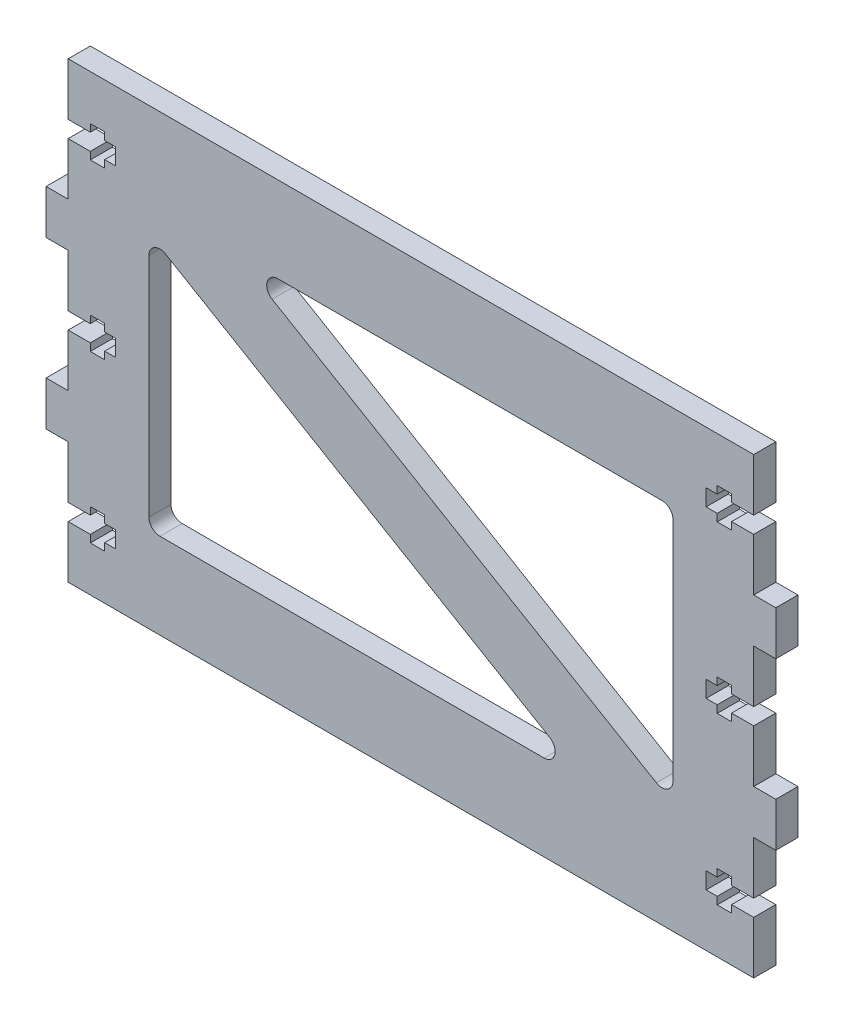
SolidWorks part; units mm, degrees
ref_plane "前视基准面" through (0, 0, 0) normal (0, 0, 1) x (1, 0, 0)
ref_plane "上视基准面" through (0, 0, 0) normal (0, 1, 0) x (1, 0, 0)
ref_plane "右视基准面" through (0, 0, 0) normal (1, 0, 0) x (0, 0, -1)
sketch "草图1" plane through (0, 0, 0) normal (0, 0, 1) x (1, 0, 0)
  line L0 (54.5343, 5.23) -> (-69.4657, 5.23) construction
  line L1 (58.5343, 20.23) -> (56.8313, 20.23) construction
  line L2 (46.9343, -24.77) -> (49.8557, -24.77) construction
  line L3 (59.5343, -9.77) -> (57.8313, -9.77) construction
  line L4 (54.5343, 3.73) -> (54.5343, 6.73) construction
  line L5 (54.5343, 5.23) -> (55.8421, 5.23) construction
  line L6 (54.5343, 6.73) -> (50.5343, 6.73)
  line L7 (50.5343, 6.73) -> (50.5343, 8.08)
  line L8 (50.5343, 8.08) -> (47.9343, 8.08)
  line L9 (47.9343, 8.08) -> (47.9343, 6.73)
  line L10 (47.9343, 6.73) -> (45.9343, 6.73)
  line L11 (47.9343, 2.38) -> (47.9343, 3.73)
  line L12 (50.5343, 3.73) -> (50.5343, 2.38)
  line L13 (47.9343, 3.73) -> (45.9343, 3.73)
  line L14 (50.5343, 2.38) -> (47.9343, 2.38)
  line L15 (54.5343, 3.73) -> (50.5343, 3.73)
  line L16 (54.5343, 24.23) -> (58.5343, 24.23)
  line L17 (58.5343, 24.23) -> (58.5343, 16.23)
  line L18 (58.5343, 16.23) -> (54.5343, 16.23)
  line L19 (54.5343, 16.23) -> (54.5343, 6.73)
  line L20 (-7.4657, 5.23) -> (-7.4657, 11.8034) construction
  line L21 (54.5343, 6.73) -> (50.5343, 6.73)
  line L22 (50.5343, 8.08) -> (47.9343, 8.08)
  line L23 (54.5343, 6.73) -> (50.5343, 6.73)
  line L24 (50.5343, 6.73) -> (50.5343, 8.08)
  line L25 (50.5343, 8.08) -> (47.9343, 8.08)
  line L26 (47.9343, 8.08) -> (47.9343, 6.73)
  line L27 (47.9343, 6.73) -> (45.9343, 6.73)
  line L28 (47.9343, 2.38) -> (47.9343, 3.73)
  line L29 (50.5343, 3.73) -> (50.5343, 2.38)
  line L30 (47.9343, 3.73) -> (45.9343, 3.73)
  line L31 (50.5343, 2.38) -> (47.9343, 2.38)
  line L32 (54.5343, 3.73) -> (50.5343, 3.73)
  line L33 (47.9343, 6.73) -> (45.9343, 6.73)
  line L34 (50.5343, 6.73) -> (50.5343, 8.08)
  line L35 (47.9343, 8.08) -> (47.9343, 6.73)
  line L36 (47.9343, 3.73) -> (45.9343, 3.73)
  line L37 (47.9343, 2.38) -> (47.9343, 3.73)
  line L38 (50.5343, 2.38) -> (47.9343, 2.38)
  line L39 (50.5343, 3.73) -> (50.5343, 2.38)
  line L40 (54.5343, 3.73) -> (50.5343, 3.73)
  line L41 (54.5343, -23.27) -> (54.5343, -13.77)
  line L42 (50.5343, -23.27) -> (54.5343, -23.27)
  line L43 (50.5343, -26.27) -> (54.5343, -26.27)
  line L44 (54.5343, -35.77) -> (54.5343, -26.27)
  line L45 (50.5343, -23.27) -> (50.5343, -21.92)
  line L46 (50.5343, -21.92) -> (47.9343, -21.92)
  line L47 (47.9343, -21.92) -> (47.9343, -23.27)
  line L48 (47.9343, -23.27) -> (45.9343, -23.27)
  line L49 (45.9343, -23.27) -> (45.9343, -26.27)
  line L50 (47.9343, -27.62) -> (47.9343, -26.27)
  line L51 (50.5343, -26.27) -> (50.5343, -27.62)
  line L52 (47.9343, -26.27) -> (45.9343, -26.27)
  line L53 (50.5343, -27.62) -> (47.9343, -27.62)
  line L54 (54.5343, -5.77) -> (54.5343, 3.73)
  line L55 (58.5343, -5.77) -> (54.5343, -5.77)
  line L56 (58.5343, -13.77) -> (58.5343, -5.77)
  line L57 (54.5343, -13.77) -> (58.5343, -13.77)
  line L58 (54.5343, 6.73) -> (50.5343, 6.73)
  line L59 (50.5343, 8.08) -> (47.9343, 8.08)
  line L60 (47.9343, 6.73) -> (45.9343, 6.73)
  line L61 (50.5343, 6.73) -> (50.5343, 8.08)
  line L62 (47.9343, 8.08) -> (47.9343, 6.73)
  line L63 (45.9343, 3.73) -> (45.9343, 6.73)
  line L64 (47.9343, 3.73) -> (45.9343, 3.73)
  line L65 (47.9343, 2.38) -> (47.9343, 3.73)
  line L66 (50.5343, 2.38) -> (47.9343, 2.38)
  line L67 (50.5343, 3.73) -> (50.5343, 2.38)
  line L68 (54.5343, 3.73) -> (50.5343, 3.73)
  line L69 (46.9343, 35.23) -> (49.8557, 35.23) construction
  line L70 (50.5343, 38.08) -> (47.9343, 38.08)
  line L71 (47.9343, 36.73) -> (45.9343, 36.73)
  line L72 (50.5343, 36.73) -> (50.5343, 38.08)
  line L73 (47.9343, 38.08) -> (47.9343, 36.73)
  line L74 (45.9343, 33.73) -> (45.9343, 36.73)
  line L75 (47.9343, 33.73) -> (45.9343, 33.73)
  line L76 (47.9343, 32.38) -> (47.9343, 33.73)
  line L77 (50.5343, 32.38) -> (47.9343, 32.38)
  line L78 (50.5343, 33.73) -> (50.5343, 32.38)
  line L79 (54.5343, 46.23) -> (54.5343, 36.73)
  line L80 (50.5343, 36.73) -> (54.5343, 36.73)
  line L81 (50.5343, 33.73) -> (54.5343, 33.73)
  line L82 (54.5343, 33.73) -> (54.5343, 24.23)
  line L83 (-61.8657, 35.23) -> (-64.7872, 35.23) construction
  line L84 (-69.4657, 5.23) -> (-70.7735, 5.23) construction
  line L85 (-69.4657, 3.73) -> (-69.4657, 6.73) construction
  line L86 (-74.4657, -9.77) -> (-72.7628, -9.77) construction
  line L87 (-61.8657, -24.77) -> (-64.7872, -24.77) construction
  line L88 (-73.4657, 20.23) -> (-71.7628, 20.23) construction
  line L89 (-69.4657, 33.73) -> (-69.4657, 24.23)
  line L90 (-65.4657, 33.73) -> (-69.4657, 33.73)
  line L91 (-65.4657, 36.73) -> (-69.4657, 36.73)
  line L92 (-69.4657, 46.23) -> (-69.4657, 36.73)
  line L93 (-65.4657, 33.73) -> (-65.4657, 32.38)
  line L94 (-65.4657, 32.38) -> (-62.8657, 32.38)
  line L95 (-62.8657, 32.38) -> (-62.8657, 33.73)
  line L96 (-62.8657, 33.73) -> (-60.8657, 33.73)
  line L97 (-60.8657, 33.73) -> (-60.8657, 36.73)
  line L98 (-62.8657, 38.08) -> (-62.8657, 36.73)
  line L99 (-65.4657, 36.73) -> (-65.4657, 38.08)
  line L100 (-62.8657, 36.73) -> (-60.8657, 36.73)
  line L101 (-65.4657, 38.08) -> (-62.8657, 38.08)
  line L102 (-69.4657, 3.73) -> (-65.4657, 3.73)
  line L103 (-65.4657, 3.73) -> (-65.4657, 2.38)
  line L104 (-65.4657, 2.38) -> (-62.8657, 2.38)
  line L105 (-62.8657, 2.38) -> (-62.8657, 3.73)
  line L106 (-62.8657, 3.73) -> (-60.8657, 3.73)
  line L107 (-60.8657, 3.73) -> (-60.8657, 6.73)
  line L108 (-62.8657, 8.08) -> (-62.8657, 6.73)
  line L109 (-65.4657, 6.73) -> (-65.4657, 8.08)
  line L110 (-62.8657, 6.73) -> (-60.8657, 6.73)
  line L111 (-65.4657, 8.08) -> (-62.8657, 8.08)
  line L112 (-69.4657, 6.73) -> (-65.4657, 6.73)
  line L113 (-69.4657, -13.77) -> (-73.4657, -13.77)
  line L114 (-73.4657, -13.77) -> (-73.4657, -5.77)
  line L115 (-73.4657, -5.77) -> (-69.4657, -5.77)
  line L116 (-69.4657, -5.77) -> (-69.4657, 3.73)
  line L117 (-65.4657, -27.62) -> (-62.8657, -27.62)
  line L118 (-62.8657, -26.27) -> (-60.8657, -26.27)
  line L119 (-65.4657, -26.27) -> (-65.4657, -27.62)
  line L120 (-62.8657, -27.62) -> (-62.8657, -26.27)
  line L121 (-60.8657, -23.27) -> (-60.8657, -26.27)
  line L122 (-62.8657, -23.27) -> (-60.8657, -23.27)
  line L123 (-62.8657, -21.92) -> (-62.8657, -23.27)
  line L124 (-65.4657, -21.92) -> (-62.8657, -21.92)
  line L125 (-65.4657, -23.27) -> (-65.4657, -21.92)
  line L126 (-69.4657, -35.77) -> (-69.4657, -26.27)
  line L127 (-65.4657, -26.27) -> (-69.4657, -26.27)
  line L128 (-65.4657, -23.27) -> (-69.4657, -23.27)
  line L129 (-69.4657, -23.27) -> (-69.4657, -13.77)
  line L130 (-69.4657, 3.73) -> (-65.4657, 3.73)
  line L131 (-65.4657, 3.73) -> (-65.4657, 2.38)
  line L132 (-65.4657, 2.38) -> (-62.8657, 2.38)
  line L133 (-62.8657, 2.38) -> (-62.8657, 3.73)
  line L134 (-62.8657, 3.73) -> (-60.8657, 3.73)
  line L135 (-62.8657, 8.08) -> (-62.8657, 6.73)
  line L136 (-65.4657, 6.73) -> (-65.4657, 8.08)
  line L137 (-62.8657, 6.73) -> (-60.8657, 6.73)
  line L138 (-69.4657, 3.73) -> (-65.4657, 3.73)
  line L139 (-65.4657, 2.38) -> (-62.8657, 2.38)
  line L140 (-62.8657, 3.73) -> (-60.8657, 3.73)
  line L141 (-65.4657, 3.73) -> (-65.4657, 2.38)
  line L142 (-62.8657, 2.38) -> (-62.8657, 3.73)
  line L143 (-62.8657, 6.73) -> (-60.8657, 6.73)
  line L144 (-62.8657, 8.08) -> (-62.8657, 6.73)
  line L145 (-65.4657, 8.08) -> (-62.8657, 8.08)
  line L146 (-65.4657, 6.73) -> (-65.4657, 8.08)
  line L147 (-69.4657, 6.73) -> (-65.4657, 6.73)
  line L148 (-65.4657, 8.08) -> (-62.8657, 8.08)
  line L149 (-69.4657, 6.73) -> (-65.4657, 6.73)
  line L150 (-69.4657, 16.23) -> (-69.4657, 6.73)
  line L151 (-73.4657, 16.23) -> (-69.4657, 16.23)
  line L152 (-73.4657, 24.23) -> (-73.4657, 16.23)
  line L153 (-69.4657, 24.23) -> (-73.4657, 24.23)
  line L154 (-69.4657, 3.73) -> (-65.4657, 3.73)
  line L155 (-65.4657, 2.38) -> (-62.8657, 2.38)
  line L156 (-62.8657, 3.73) -> (-60.8657, 3.73)
  line L157 (-65.4657, 3.73) -> (-65.4657, 2.38)
  line L158 (-62.8657, 2.38) -> (-62.8657, 3.73)
  line L159 (-62.8657, 6.73) -> (-60.8657, 6.73)
  line L160 (-62.8657, 8.08) -> (-62.8657, 6.73)
  line L161 (-65.4657, 8.08) -> (-62.8657, 8.08)
  line L162 (-65.4657, 6.73) -> (-65.4657, 8.08)
  line L163 (-69.4657, 6.73) -> (-65.4657, 6.73)
  line L164 (-69.4657, 46.23) -> (54.5343, 46.23)
  line L165 (54.5343, -35.77) -> (-69.4657, -35.77)
  dimension "D1" = 3
  dimension "D2" = 15
  dimension "D3" = 62
extrude "凸台-拉伸1" add sketch "草图1" along normal blind 4
sketch "草图2" plane through (54.5343, 0, 0) normal (1, 0, 0) x (0, 0, -1)
  line L0 (-2, -26.27) -> (-2, -23.27)
  line L1 (-4, -26.27) -> (0, -26.27) construction
  line L2 (-4, -23.27) -> (0, -23.27) construction
  circle A0 centre (-2, -24.77) radius 1.5
sketch "草图3" plane through (0, 0, 4) normal (0, 0, 1) x (1, 0, 0)
  line L23 (-60.8657, 36.73) -> (-60.8657, -26.27) construction
  line L24 (-60.8657, -26.27) -> (45.9343, -26.27) construction
  line L26 (45.9343, -26.27) -> (-60.8657, 36.73) construction
  line L33 (17.6429, -16.5474) -> (-51.8496, 24.4454)
  line L34 (-54.8657, 22.7227) -> (-54.8657, -18.27)
  line L35 (-52.8657, -20.27) -> (16.6267, -20.27)
  line L36 (-60.8657, 36.73) -> (45.9343, 36.73) construction
  line L37 (45.9343, 36.73) -> (45.9343, -26.27) construction
  line L38 (-31.5582, 30.73) -> (37.9343, 30.73)
  line L39 (39.9343, 28.73) -> (39.9343, -12.2627)
  line L40 (36.9181, -13.9854) -> (-32.5743, 27.0074)
  line L41 (39.9343, 30.73) -> (39.9343, -15.7646) construction
  line L42 (-38.8851, 30.73) -> (39.9343, 30.73) construction
  line L43 (39.9343, -15.7646) -> (-38.8851, 30.73) construction
  line L44 (23.9536, -20.27) -> (-54.8657, 26.2246) construction
  line L45 (-54.8657, -20.27) -> (23.9536, -20.27) construction
  line L46 (-54.8657, 26.2246) -> (-54.8657, -20.27) construction
  arc A0 (39.9343, 28.73) -> (37.9343, 30.73) centre (37.9343, 28.73) ccw
  arc A1 (39.9343, -12.2627) -> (36.9181, -13.9854) centre (37.9343, -12.2627) cw
  arc A2 (-31.5582, 30.73) -> (-32.5743, 27.0074) centre (-31.5582, 28.73) ccw
  arc A3 (17.6429, -16.5474) -> (16.6267, -20.27) centre (16.6267, -18.27) cw
  arc A4 (-52.8657, -20.27) -> (-54.8657, -18.27) centre (-52.8657, -18.27) cw
  arc A5 (-51.8496, 24.4454) -> (-54.8657, 22.7227) centre (-52.8657, 22.7227) ccw
  dimension "D1" = 6
  dimension "D3" = 2
  dimension "D2" = 6
extrude "切除-拉伸1" cut sketch "草图3" against normal blind 10
